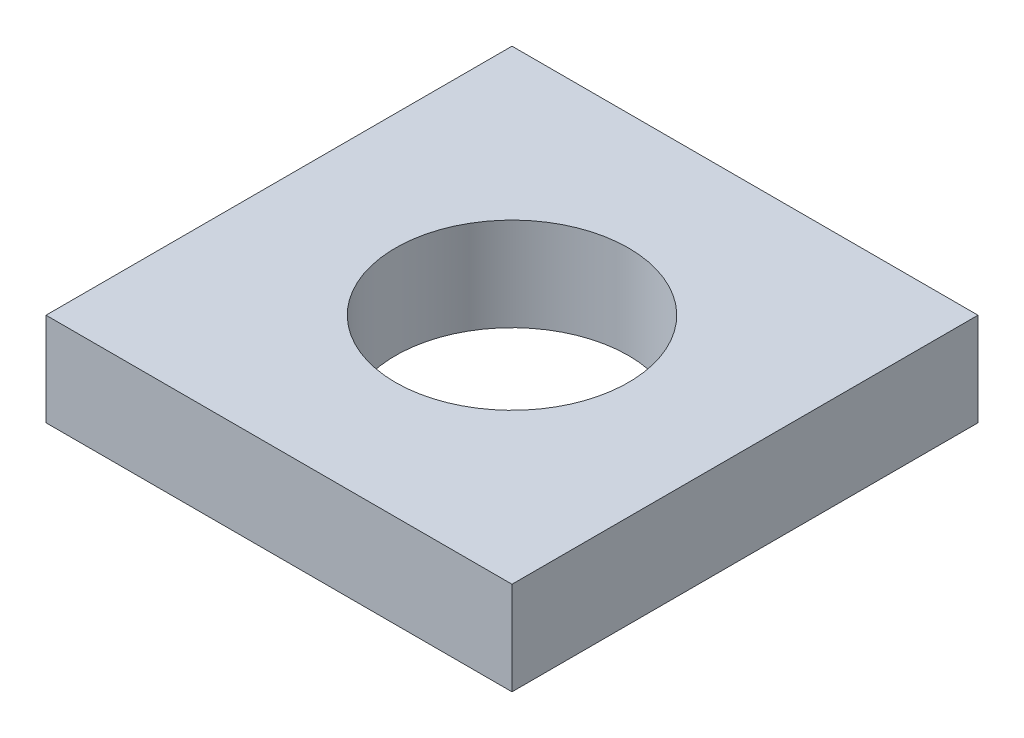
SolidWorks part; units mm, degrees
ref_plane "Front Plane" through (0, 0, 0) normal (0, 0, 1) x (1, 0, 0)
ref_plane "Top Plane" through (0, 0, 0) normal (0, 1, 0) x (1, 0, 0)
ref_plane "Right Plane" through (0, 0, 0) normal (1, 0, 0) x (0, 0, -1)
sketch "Sketch1" plane through (0, 0, 0) normal (0, 1, 0) x (1, 0, 0)
  line L1 (-6.35, -6.35) -> (6.35, -6.35)
  line L2 (-6.35, -6.35) -> (-6.35, 6.35)
  line L3 (-6.35, 6.35) -> (6.35, 6.35)
  line L4 (6.35, -6.35) -> (6.35, 6.35)
  line L5 (-6.35, -6.35) -> (6.35, 6.35) construction
  line L6 (-6.35, 6.35) -> (6.35, -6.35) construction
  circle A0 centre (0, 0) radius 3.175
  point P0 (0, 0)
  dimension "D1" = 6.35
  dimension "D2" = 12.7
  dimension "D3" = 12.7
extrude "Boss-Extrude1" add sketch "Sketch1" along normal blind 2.54 contours L1 L4 L3 L2 A0
